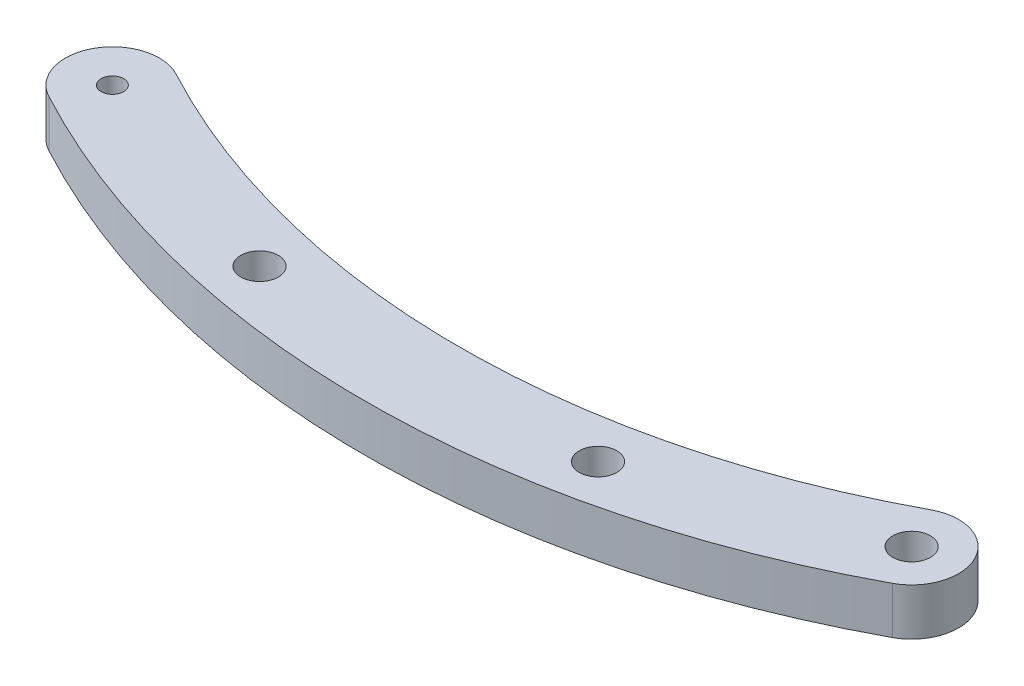
SolidWorks part; units mm, degrees
ref_plane "Front Plane" through (0, 0, 0) normal (0, 0, 1) x (1, 0, 0)
ref_plane "Top Plane" through (0, 0, 0) normal (0, 1, 0) x (1, 0, 0)
ref_plane "Right Plane" through (0, 0, 0) normal (1, 0, 0) x (0, 0, -1)
sketch "Sketch1" plane through (0, 0, 0) normal (0, 1, 0) x (1, 0, 0)
  circle A0 centre (0, 0) radius 2.5
  circle A1 centre (42.5, 0) radius 2.5
  arc A2 (0, 0) -> (42.5, 0) centre (21.25, -39.6666) cw construction
  arc A3 (1.1806, -2.2037) -> (41.3194, -2.2037) centre (21.25, -39.6666) cw
  arc A4 (-1.1806, 2.2037) -> (43.6806, 2.2037) centre (21.25, -39.6666) cw
  circle A5 centre (0, 0) radius 0.6
  circle A6 centre (42.5, 0) radius 1
  dimension "D1" = 45
  dimension "D5" = 1.2
  dimension "D6" = 2
  dimension "D4" = 42.5
  dimension "D2" = 2.5
  dimension "D3" = 2.5
extrude "Boss-Extrude1" add sketch "Sketch1" along normal blind 2.5 contours A0 A5 | A4 A0 A3 A1 | A1 A6
sketch "Sketch2" plane through (0, 2.5, 0) normal (0, 1, 0) x (1, 0, 0)
  arc A0 (0, 0) -> (42.5, 0) centre (21.25, -39.6666) cw construction
  circle A1 centre (12.25, 4.4242) radius 1
  circle A2 centre (30.25, 4.4242) radius 1
  dimension "D1" = 45
  dimension "D2" = 18
  dimension "D3" = 2
extrude "Cut-Extrude1" cut sketch "Sketch2" against normal through all
mirror "Mirror1" about plane through (0, 0, 0) normal (0, 0, 1) of bodies 102
delete or keep bodies "Body-Delete/Keep 1" type delete bodies bodies 102
